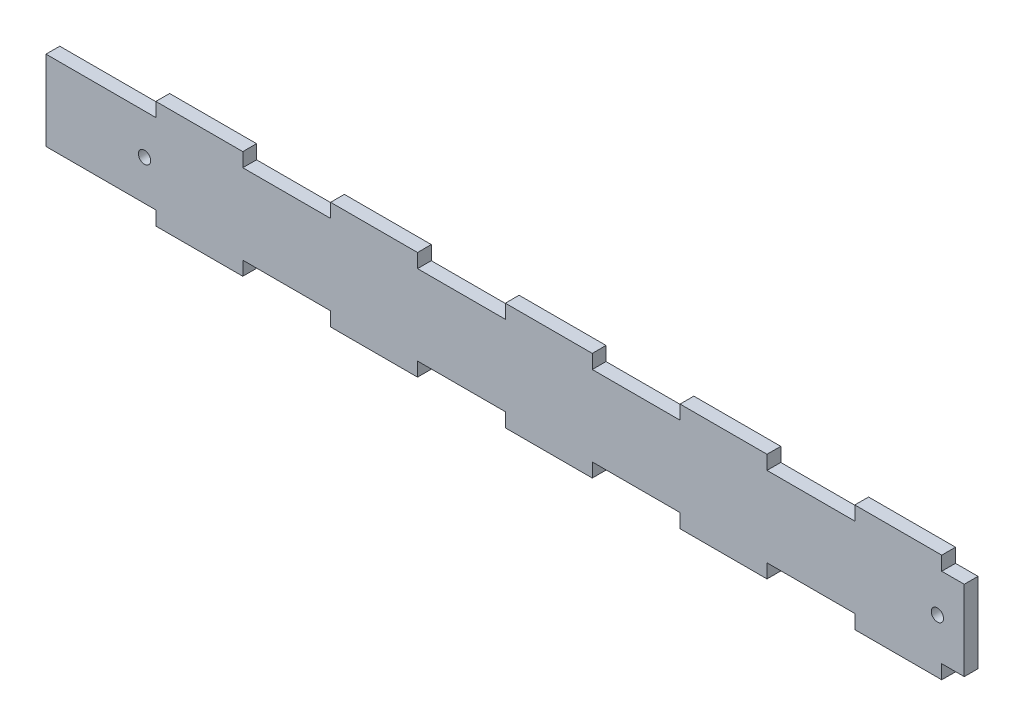
SolidWorks part; units mm, degrees
ref_plane "Front Plane" through (0, 0, 0) normal (0, 0, 1) x (1, 0, 0)
ref_plane "Top Plane" through (0, 0, 0) normal (0, 1, 0) x (1, 0, 0)
ref_plane "Right Plane" through (0, 0, 0) normal (1, 0, 0) x (0, 0, -1)
sketch "Sketch1" plane through (0, 0, 0) normal (0, 0, 1) x (1, 0, 0)
  line L0 (-60.6717, -7.3398) -> (-35.5217, -7.3398)
  line L1 (-60.6717, -7.3398) -> (-60.6717, 10.9802)
  line L2 (-35.5217, -10.5398) -> (-35.5217, -7.3898)
  line L3 (-15.6217, -10.5398) -> (-35.5717, -10.5398)
  line L4 (144.4283, 14.1802) -> (124.4283, 14.1802) construction
  line L5 (124.4283, 14.1802) -> (124.4283, 11.0302) construction
  line L6 (-15.6217, -7.3398) -> (-15.6217, -10.5398)
  line L7 (144.4283, 11.0302) -> (144.4283, 14.1802) construction
  line L8 (104.4283, 14.1802) -> (84.4283, 14.1802) construction
  line L9 (84.4283, 14.1802) -> (84.4283, 11.0302) construction
  line L10 (-60.6717, 1.8202) -> (149.5283, 1.8202) construction
  line L11 (104.4283, 11.0302) -> (104.4283, 14.1802) construction
  line L12 (-15.6217, -7.3398) -> (4.4783, -7.3398)
  line L13 (24.4283, -7.3898) -> (44.4283, -7.3898) construction
  line L14 (144.4283, -7.3898) -> (149.5283, -7.3898) construction
  line L15 (84.4283, -7.3898) -> (64.4283, -7.3898) construction
  line L16 (64.4283, 14.1802) -> (44.4283, 14.1802) construction
  line L17 (44.4283, 14.1802) -> (44.4283, 11.0302) construction
  line L18 (104.4283, -7.3898) -> (124.4283, -7.3898) construction
  line L19 (64.4283, 11.0302) -> (64.4283, 14.1802) construction
  line L20 (24.4283, -7.3898) -> (24.4283, -10.5398) construction
  line L21 (-35.5717, -7.3898) -> (-35.5717, -10.5398) construction
  line L22 (-35.5217, 10.9802) -> (-35.5217, 14.1802)
  line L23 (64.4283, -7.3898) -> (64.4283, -10.5398) construction
  line L24 (24.4283, 14.1802) -> (4.4283, 14.1802) construction
  line L25 (4.4283, 14.1802) -> (4.4283, 11.0302) construction
  line L26 (-60.6717, 10.9802) -> (-35.5217, 10.9802)
  line L27 (24.4283, 11.0302) -> (24.4283, 14.1802) construction
  line L28 (44.4283, -10.5398) -> (44.4283, -7.3898) construction
  line L29 (64.4283, -10.5398) -> (44.4283, -10.5398) construction
  line L31 (104.4283, -7.3898) -> (104.4283, -10.5398) construction
  line L32 (84.4283, -10.5398) -> (84.4283, -7.3898) construction
  line L33 (104.4283, -10.5398) -> (84.4283, -10.5398) construction
  line L34 (-15.6217, 14.1802) -> (-35.5717, 14.1802)
  line L35 (144.4283, -7.3898) -> (144.4283, -10.5398) construction
  line L36 (-15.5717, 14.1802) -> (-35.5717, 14.1802) construction
  line L37 (-35.5717, 14.1802) -> (-35.5717, 11.0302) construction
  line L38 (-15.6217, 10.9802) -> (-15.6217, 14.1802)
  line L39 (-15.5717, 11.0302) -> (-15.5717, 14.1802) construction
  line L40 (124.4283, -10.5398) -> (124.4283, -7.3898) construction
  line L41 (144.4283, -10.5398) -> (124.4283, -10.5398) construction
  line L42 (144.3783, -7.3398) -> (144.4625, -7.3398)
  line L43 (144.3783, -7.3898) -> (144.3783, -7.3398)
  line L44 (144.4283, 14.1802) -> (124.4283, 14.1802) construction
  line L45 (124.4283, 14.1802) -> (124.4283, 11.0302) construction
  line L46 (144.4625, -7.3398) -> (149.5283, -7.3398)
  line L47 (144.4283, 11.0302) -> (144.4283, 14.1802) construction
  line L48 (104.4283, 14.1802) -> (84.4283, 14.1802) construction
  line L49 (84.4283, 14.1802) -> (84.4283, 11.0302) construction
  line L50 (144.3783, -7.3898) -> (144.3783, -10.5398)
  line L51 (104.4283, 11.0302) -> (104.4283, 14.1802) construction
  line L52 (144.3783, -10.5398) -> (124.4783, -10.5398)
  line L53 (124.4783, -10.5398) -> (124.4783, -7.3398)
  line L54 (-15.6217, 10.9802) -> (4.4783, 10.9802)
  line L55 (104.3783, -7.3398) -> (124.4783, -7.3398)
  line L56 (64.4283, 14.1802) -> (44.4283, 14.1802) construction
  line L57 (44.4283, 14.1802) -> (44.4283, 11.0302) construction
  line L58 (4.4783, 14.1802) -> (4.4783, 10.9802)
  line L59 (64.4283, 11.0302) -> (64.4283, 14.1802) construction
  line L60 (104.3783, -7.3398) -> (104.3783, -10.5398)
  line L61 (104.3783, -10.5398) -> (84.4783, -10.5398)
  line L62 (24.3783, 14.1802) -> (4.4783, 14.1802)
  line L63 (84.4783, -10.5398) -> (84.4783, -7.3398)
  line L64 (24.4283, 14.1802) -> (4.4283, 14.1802) construction
  line L65 (4.4283, 14.1802) -> (4.4283, 11.0302) construction
  line L66 (144.4283, 14.1802) -> (144.4283, 11.0302) construction
  line L67 (24.4283, 11.0302) -> (24.4283, 14.1802) construction
  line L68 (84.4783, -7.3398) -> (64.3783, -7.3398)
  line L69 (144.4283, -10.5398) -> (144.4283, -7.3898)
  line L70 (144.4283, 11.0302) -> (149.5283, 11.0302) construction
  line L71 (64.3783, -7.3398) -> (64.3783, -10.5398)
  line L72 (64.3783, -10.5398) -> (44.4783, -10.5398)
  line L73 (44.4783, -10.5398) -> (44.4783, -7.3398)
  line L74 (24.3783, 10.9802) -> (24.3783, 14.1802)
  line L75 (24.3783, -7.3398) -> (44.4783, -7.3398)
  line L76 (-15.5717, 14.1802) -> (-35.5717, 14.1802) construction
  line L77 (-35.5717, 14.1802) -> (-35.5717, 11.0302) construction
  line L78 (24.3783, -7.3398) -> (24.3783, -10.5398)
  line L79 (-15.5717, 11.0302) -> (-15.5717, 14.1802) construction
  line L80 (24.3783, 10.9802) -> (44.4783, 10.9802)
  line L81 (24.3783, -10.5398) -> (4.4783, -10.5398)
  line L82 (4.4783, -10.5398) -> (4.4783, -7.3398)
  line L83 (44.4783, 14.1802) -> (44.4783, 10.9802)
  line L84 (-60.6717, -10.5398) -> (-60.6717, 14.1802) construction
  line L85 (-35.5717, 11.0302) -> (-35.5717, 14.1802) construction
  line L86 (64.3783, 14.1802) -> (44.4783, 14.1802)
  line L87 (64.3783, 10.9802) -> (64.3783, 14.1802)
  line L88 (-35.5217, -7.3898) -> (-35.5217, -7.3398)
  line L89 (-35.5717, -10.5398) -> (-35.5217, -10.5398)
  line L90 (-35.5217, 10.9802) -> (-35.5717, 10.9802)
  line L91 (-35.5717, 10.9802) -> (-35.5717, 11.0302)
  line L93 (-35.5717, 11.0302) -> (-35.5717, 14.1802)
  line L94 (104.4283, 11.0302) -> (124.4283, 11.0302) construction
  line L95 (84.4283, 11.0302) -> (64.4283, 11.0302) construction
  line L96 (144.4283, 14.1802) -> (144.4283, 11.0302) construction
  line L97 (144.4283, 11.0302) -> (149.5283, 11.0302) construction
  line L98 (24.4283, 11.0302) -> (44.4283, 11.0302) construction
  line L99 (-15.5717, 11.0302) -> (4.4283, 11.0302) construction
  line L100 (84.4783, 10.9802) -> (64.3783, 10.9802)
  line L101 (84.4783, 14.1802) -> (84.4783, 10.9802)
  line L102 (104.3783, 14.1802) -> (84.4783, 14.1802)
  line L103 (104.3783, 10.9802) -> (104.3783, 14.1802)
  line L104 (104.3783, 10.9802) -> (124.4783, 10.9802)
  line L105 (124.4783, 14.1802) -> (124.4783, 10.9802)
  line L106 (144.3783, 14.1802) -> (124.4783, 14.1802)
  line L107 (144.3783, 11.0302) -> (144.3783, 14.1802)
  line L108 (144.4625, 10.9802) -> (149.5283, 10.9802)
  line L109 (149.5283, 10.9802) -> (149.5283, -7.3398)
  line L111 (144.3783, 11.0302) -> (144.3783, 10.9802)
  line L112 (144.3783, 10.9802) -> (144.4625, 10.9802)
  circle A1 centre (-38.1217, 1.8202) radius 1.4
  dimension "D1" = 0.05
  dimension "D2" = 0.05
  dimension "D3" = 3.15
  dimension "D4" = 0.05
extrude "Boss-Extrude1" add sketch "Sketch1" along normal blind 3.15 contours L112 L111 L107 L106 L105 L104 L103 L102 L101 L100 L87 L86 L83 L80 L74 L62 L58 L54 L38 L34 L93 L91 L90 L26 L1 L0 L88 L2 L89 L3 L6 L12 L82 L81 L78 L75 L73 L72 L71 L68 L63 L61 L60 L55 L53 L52 L50 L43 L42 L46 L109
sketch "Sketch2" plane through (0, 0, 3.15) normal (0, 0, 1) x (1, 0, 0)
  line L0 (137.2421, 11.0302) -> (137.2421, -7.3898) construction
  line L1 (137.2421, 11.0302) -> (137.2421, -7.3898) construction
  line L2 (137.2421, 1.8202) -> (149.5283, 1.8202) construction
  line L3 (149.5283, 11.0302) -> (149.5283, -7.3898) construction
  circle A0 centre (143.3852, 1.8202) radius 1.4
  dimension "D1" = 2.8
extrude "Cut-Extrude1" cut sketch "Sketch2" against normal blind 10
sketch "Sketch3" plane through (0, 0, 3.15) normal (0, 0, 1) x (1, 0, 0)
  line L44 (149.5283, 10.9802) -> (144.3783, 10.9802)
  line L45 (144.3783, 10.9802) -> (144.3783, 14.1802)
  line L46 (144.3783, 14.1802) -> (124.4783, 14.1802)
  line L47 (124.4783, 14.1802) -> (124.4783, 10.9802)
  line L48 (124.4783, 10.9802) -> (104.3783, 10.9802)
  line L49 (104.3783, 10.9802) -> (104.3783, 14.1802)
  line L50 (104.3783, 14.1802) -> (84.4783, 14.1802)
  line L51 (84.4783, 14.1802) -> (84.4783, 10.9802)
  line L52 (84.4783, 10.9802) -> (64.3783, 10.9802)
  line L53 (64.3783, 10.9802) -> (64.3783, 14.1802)
  line L54 (64.3783, 14.1802) -> (44.4783, 14.1802)
  line L55 (44.4783, 14.1802) -> (44.4783, 10.9802)
  line L56 (44.4783, 10.9802) -> (24.3783, 10.9802)
  line L57 (24.3783, 10.9802) -> (24.3783, 14.1802)
  line L58 (24.3783, 14.1802) -> (4.4783, 14.1802)
  line L59 (4.4783, 14.1802) -> (4.4783, 10.9802)
  line L60 (4.4783, 10.9802) -> (-15.6217, 10.9802)
  line L61 (-15.6217, 10.9802) -> (-15.6217, 14.1802)
  line L62 (-15.6217, 14.1802) -> (-35.5217, 14.1802)
  line L63 (-35.5217, 14.1802) -> (-35.5217, 10.9802)
  line L64 (-35.5217, 10.9802) -> (-60.6717, 10.9802)
  line L65 (-60.6717, 10.9802) -> (-60.6717, -7.3398)
  line L66 (-60.6717, -7.3398) -> (-35.5217, -7.3398)
  line L67 (-35.5217, -7.3398) -> (-35.5217, -10.5398)
  line L68 (-35.5217, -10.5398) -> (-15.6217, -10.5398)
  line L69 (-15.6217, -10.5398) -> (-15.6217, -7.3398)
  line L70 (-15.6217, -7.3398) -> (4.4783, -7.3398)
  line L71 (4.4783, -7.3398) -> (4.4783, -10.5398)
  line L72 (4.4783, -10.5398) -> (24.3783, -10.5398)
  line L73 (24.3783, -10.5398) -> (24.3783, -7.3398)
  line L74 (24.3783, -7.3398) -> (44.4783, -7.3398)
  line L75 (44.4783, -7.3398) -> (44.4783, -10.5398)
  line L76 (44.4783, -10.5398) -> (64.3783, -10.5398)
  line L77 (64.3783, -10.5398) -> (64.3783, -7.3398)
  line L78 (64.3783, -7.3398) -> (84.4783, -7.3398)
  line L79 (84.4783, -7.3398) -> (84.4783, -10.5398)
  line L80 (84.4783, -10.5398) -> (104.3783, -10.5398)
  line L81 (104.3783, -10.5398) -> (104.3783, -7.3398)
  line L82 (104.3783, -7.3398) -> (124.4783, -7.3398)
  line L83 (124.4783, -7.3398) -> (124.4783, -10.5398)
  line L84 (124.4783, -10.5398) -> (144.3783, -10.5398)
  line L85 (144.3783, -10.5398) -> (144.3783, -7.3398)
  line L86 (144.3783, -7.3398) -> (149.5283, -7.3398)
  line L87 (149.5283, -7.3398) -> (149.5283, 10.9802)
  line L88 (149.5283, 10.9802) -> (144.3783, 10.9802)
  line L89 (144.3783, 10.9802) -> (144.3783, 14.1802)
  line L90 (144.3783, 14.1802) -> (124.4783, 14.1802)
  line L91 (124.4783, 14.1802) -> (124.4783, 10.9802)
  line L92 (124.4783, 10.9802) -> (104.3783, 10.9802)
  line L93 (104.3783, 10.9802) -> (104.3783, 14.1802)
  line L94 (104.3783, 14.1802) -> (84.4783, 14.1802)
  line L95 (84.4783, 14.1802) -> (84.4783, 10.9802)
  line L96 (84.4783, 10.9802) -> (64.3783, 10.9802)
  line L97 (64.3783, 10.9802) -> (64.3783, 14.1802)
  line L98 (64.3783, 14.1802) -> (44.4783, 14.1802)
  line L99 (44.4783, 14.1802) -> (44.4783, 10.9802)
  line L100 (44.4783, 10.9802) -> (24.3783, 10.9802)
  line L101 (24.3783, 10.9802) -> (24.3783, 14.1802)
  line L102 (24.3783, 14.1802) -> (4.4783, 14.1802)
  line L103 (4.4783, 14.1802) -> (4.4783, 10.9802)
  line L104 (4.4783, 10.9802) -> (-15.6217, 10.9802)
  line L105 (-15.6217, 10.9802) -> (-15.6217, 14.1802)
  line L106 (-15.6217, 14.1802) -> (-35.5217, 14.1802)
  line L107 (-35.5217, 14.1802) -> (-35.5217, 10.9802)
  line L108 (-35.5217, 10.9802) -> (-60.6717, 10.9802)
  line L109 (-60.6717, 10.9802) -> (-60.6717, -7.3398)
  line L110 (-60.6717, -7.3398) -> (-35.5217, -7.3398)
  line L111 (-35.5217, -7.3398) -> (-35.5217, -10.5398)
  line L112 (-35.5217, -10.5398) -> (-15.6217, -10.5398)
  line L113 (-15.6217, -10.5398) -> (-15.6217, -7.3398)
  line L114 (-15.6217, -7.3398) -> (4.4783, -7.3398)
  line L115 (4.4783, -7.3398) -> (4.4783, -10.5398)
  line L116 (4.4783, -10.5398) -> (24.3783, -10.5398)
  line L117 (24.3783, -10.5398) -> (24.3783, -7.3398)
  line L118 (24.3783, -7.3398) -> (44.4783, -7.3398)
  line L119 (44.4783, -7.3398) -> (44.4783, -10.5398)
  line L120 (44.4783, -10.5398) -> (64.3783, -10.5398)
  line L121 (64.3783, -10.5398) -> (64.3783, -7.3398)
  line L122 (64.3783, -7.3398) -> (84.4783, -7.3398)
  line L123 (84.4783, -7.3398) -> (84.4783, -10.5398)
  line L124 (84.4783, -10.5398) -> (104.3783, -10.5398)
  line L125 (104.3783, -10.5398) -> (104.3783, -7.3398)
  line L126 (104.3783, -7.3398) -> (124.4783, -7.3398)
  line L127 (124.4783, -7.3398) -> (124.4783, -10.5398)
  line L128 (124.4783, -10.5398) -> (144.3783, -10.5398)
  line L129 (144.3783, -10.5398) -> (144.3783, -7.3398)
  line L130 (144.3783, -7.3398) -> (149.5283, -7.3398)
  line L131 (149.5283, -7.3398) -> (149.5283, 10.9802)
  circle A3 centre (-38.1217, 1.8202) radius 1.4
  circle A4 centre (-38.1217, 1.8202) radius 1.4
  circle A5 centre (143.3852, 1.8202) radius 1.4
  circle A6 centre (143.3852, 1.8202) radius 1.4
  dimension "D1" = 0
  dimension "D2" = 0
  dimension "D3" = 0
